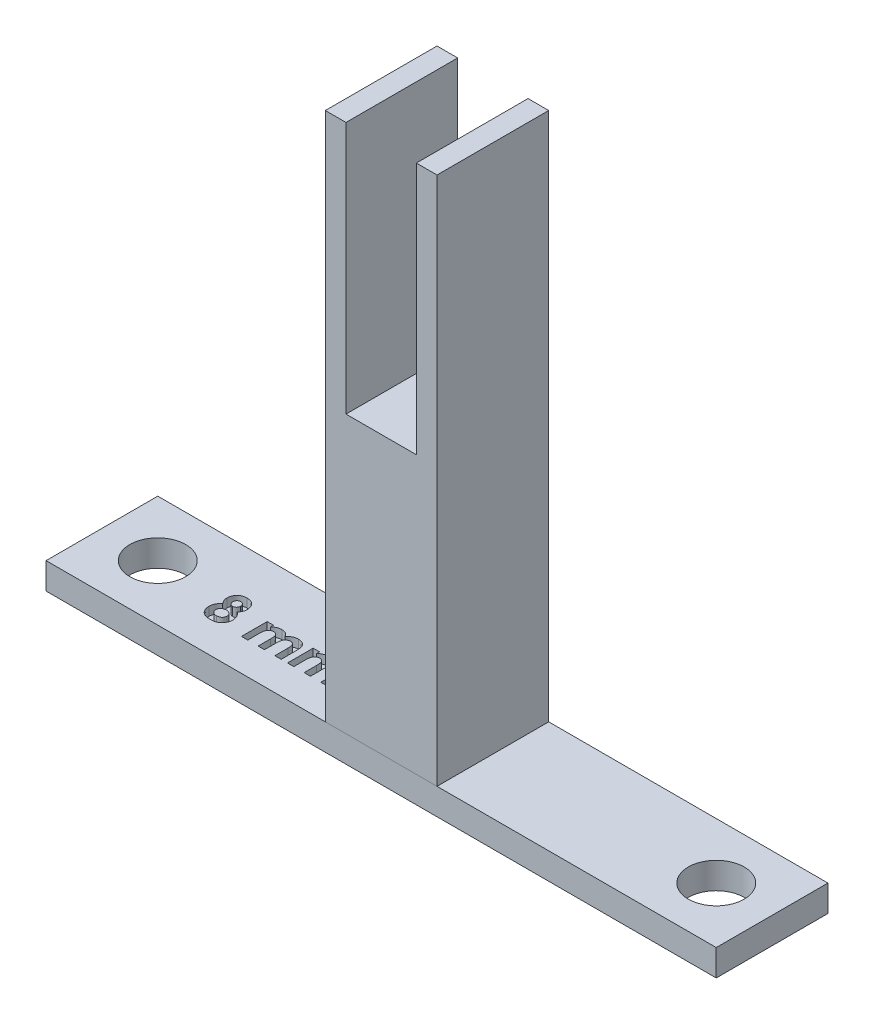
SolidWorks part; units mm, degrees
ref_plane "Front" through (0, 0, 0) normal (0, 0, 1) x (1, 0, 0)
ref_plane "Top" through (0, 0, 0) normal (0, 1, 0) x (1, 0, 0)
ref_plane "Right" through (0, 0, 0) normal (1, 0, 0) x (0, 0, -1)
other "Center of Mass"
sketch "Sketch1" plane through (0, 0, 0) normal (0, 0, 1) x (1, 0, 0)
  line L1 (0, 0) -> (12.7, 0)
  line L2 (0, 0) -> (0, 80.2)
  line L3 (0, 80.2) -> (12.7, 80.2)
  line L4 (12.7, 0) -> (12.7, 80.2)
  dimension "D1" = 80.2
  dimension "D2" = 12.7
extrude "Boss-Extrude1" add sketch "Sketch1" along normal blind 12.7
ref_point "Point1"
sketch "Sketch4" plane through (0, 0, 0) normal (0, -1, 0) x (-1, 0, 0)
  line L1 (31.7524, 0.0001) -> (-44.4476, 0.0001)
  line L2 (31.7524, 0.0001) -> (31.7524, -12.6999)
  line L3 (31.7524, -12.6999) -> (-44.4476, -12.6999)
  line L4 (-44.4476, 0.0001) -> (-44.4476, -12.6999)
  line L5 (31.7524, 0.0001) -> (-44.4476, -12.6999) construction
  line L6 (31.7524, -12.6999) -> (-44.4476, 0.0001) construction
  point P0 (-6.3476, -6.3499)
  dimension "D1" = 12.7
  dimension "D2" = 76.2
extrude "Boss-Extrude3" add sketch "Sketch4" along normal blind 3
sketch "Sketch12" plane through (0, 0, 12.7) normal (0, 0, 1) x (1, 0, 0)
  line L0 (6.35, 30) -> (6.35, 65.1) construction
  line L1 (2.35, 31.4792) -> (2.35, 62.1244)
  line L2 (10.35, 31.4792) -> (10.35, 62.1244)
  line L3 (44.4476, -3) -> (-31.7524, -3) construction
  line L5 (12.7, 80.2) -> (0, 80.2) construction
  line L6 (2.35, 31.4792) -> (10.35, 31.4792)
  arc A1 (10.35, 62.1244) -> (2.35, 62.1244) centre (6.35, 65.1) ccw
  point P2 (6.35, 47.55)
  point P9 (6.35, 31.4792)
  point P13 (6.35, 80.2)
  dimension "D1" = 33
  dimension "D2" = 8
extrude "Cut-Extrude5" cut sketch "Sketch12" against normal blind 23
sketch "Sketch17" plane through (0, 0, 0) normal (0, 1, 0) x (1, 0, 0)
  line L0 (-31.7524, 0.0001) -> (44.4476, 0.0001) construction
  line L1 (0, -12.6999) -> (-31.7524, -12.6999) construction
  circle A0 centre (-25.4024, -6.3499) radius 3.175
  point P2 (6.3476, 0.0001)
  dimension "D2" = 31.75
  dimension "D1" = 6.35
extrude "Cut-Extrude9" cut sketch "Sketch17" against normal blind 3
sketch "Sketch18" plane through (0, 0, 0) normal (0, 1, 0) x (1, 0, 0)
  line L0 (-31.7524, 0.0001) -> (44.4476, 0.0001) construction
  line L6 (12.7, -12.7) -> (0, -12.7) construction
  circle A0 centre (38.1, -6.3499) radius 3.175
  point P4 (6.35, -12.7)
  dimension "D1" = 6.35
  dimension "D2" = 31.75
extrude "Cut-Extrude10" cut sketch "Sketch18" against normal blind 3
sketch "Sketch19" plane through (0, 80.2, 0) normal (0, 1, 0) x (1, 0, 0)
  line L4 (12.7, 0) -> (0, 0)
  line L5 (0, 0) -> (0, -12.7)
  line L6 (0, -12.7) -> (12.7, -12.7)
  line L7 (12.7, -12.7) -> (12.7, 0)
  line L8 (12.7, 0) -> (0, 0)
  line L9 (0, 0) -> (0, -12.7)
  line L10 (0, -12.7) -> (12.7, -12.7)
  line L11 (12.7, -12.7) -> (12.7, 0)
  dimension "D1" = 0
extrude "Cut-Extrude11" cut sketch "Sketch19" against normal blind 20
sketch "Sketch20" plane through (0, 0, 0) normal (0, 1, 0) x (1, 0, 0)
  line L0 (0, -9.0557) -> (-18.9747, -9.0557) construction
  line L1 (0, -12.6999) -> (0, 0) construction
  text T0 "<b>8 mm  </b>" font "Century Gothic" height 4
extrude "Cut-Extrude12" cut sketch "Sketch20" against normal blind 1
